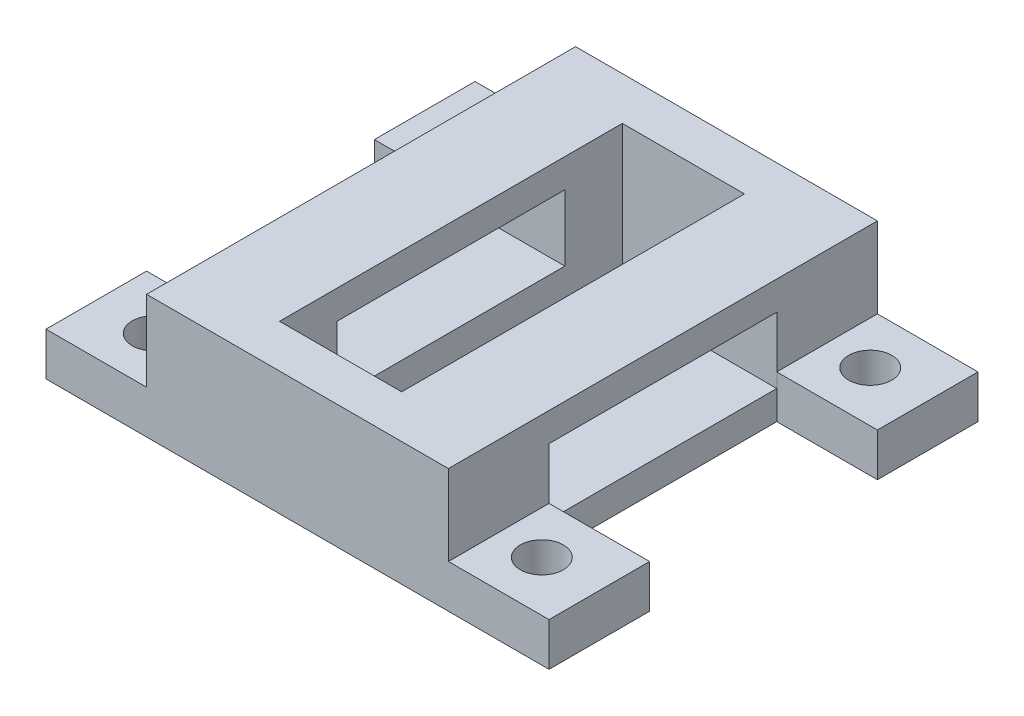
SolidWorks part; units mm, degrees
ref_plane "Front Plane" through (0, 0, 0) normal (0, 0, 1) x (1, 0, 0)
ref_plane "Top Plane" through (0, 0, 0) normal (0, 1, 0) x (1, 0, 0)
ref_plane "Right Plane" through (0, 0, 0) normal (1, 0, 0) x (0, 0, -1)
sketch "Sketch1" plane through (0, 0, 0) normal (0, 1, 0) x (1, 0, 0)
  line L8 (-10.5, 0) -> (-10.5, -24.8496)
  line L10 (10.5, 0) -> (10.5, -24.8496)
  line L11 (7.5, -29.8496) -> (-10.5, -29.8496)
  line L14 (7.5, -29.8496) -> (10.5, -29.8496)
  line L20 (10.5, 0) -> (-10.5, 0)
  line L21 (10.5, -24.8496) -> (10.5, -29.8496)
  line L22 (-10.5, -24.8496) -> (-10.5, -29.8496)
  point P0 (0, 0)
  point P1 (0, 0)
  dimension "D4" = 30
  dimension "D5" = 21
extrude "Boss-Extrude1" add sketch "Sketch1" along normal blind 8.6
sketch "Sketch5" plane through (0, 8.6, 0) normal (0, 1, 0) x (1, 0, 0)
  line L0 (10.5, 0) -> (-10.5, 0) construction
  line L1 (4.25, -26.8496) -> (-4.25, -26.8496)
  line L2 (4.25, -26.8496) -> (4.25, -2.9996)
  line L3 (4.25, -2.9996) -> (-4.25, -2.9996)
  line L4 (-4.25, -26.8496) -> (-4.25, -2.9996)
  line L8 (-10.5, -29.8496) -> (10.5, -29.8496) construction
  dimension "D1" = 3
  dimension "D2" = 23.85
  dimension "D3" = 8.5
  dimension "D4" = 6.25
  dimension "D5" = 6.25
  dimension "D6" = 2.9996
extrude "Cut-Extrude3" cut sketch "Sketch5" against normal blind 10
sketch "Sketch6" plane through (-10.5, 0, 0) normal (-1, 0, 0) x (0, 0, 1)
  line L1 (7, 2) -> (22.85, 2)
  line L2 (7, 2) -> (7, 6.6)
  line L3 (7, 6.6) -> (22.85, 6.6)
  line L4 (22.85, 2) -> (22.85, 6.6)
  line L5 (0, 0) -> (29.8496, 0) construction
  line L6 (0, 8.6) -> (29.8496, 8.6) construction
  line L7 (0, 8.6) -> (0, 0) construction
  dimension "D1" = 15.85
  dimension "D2" = 7
  dimension "D3" = 4.6
  dimension "D4" = 2
  dimension "D5" = 2
extrude "Cut-Extrude4" cut sketch "Sketch6" against normal blind 10
sketch "Sketch7" plane through (10.5, 0, 0) normal (1, 0, 0) x (0, 0, -1)
  line L1 (-22.8496, 6.6) -> (-6.9996, 6.6)
  line L2 (-22.8496, 6.6) -> (-22.8496, 2)
  line L3 (-22.8496, 2) -> (-6.9996, 2)
  line L4 (-6.9996, 6.6) -> (-6.9996, 2)
  line L5 (-29.8496, 0) -> (0, 0) construction
  line L6 (-29.8496, 8.6) -> (-29.8496, 0) construction
  line L7 (-29.8496, 8.6) -> (0, 8.6) construction
  dimension "D1" = 15.85
  dimension "D2" = 7
  dimension "D3" = 2
  dimension "D4" = 4.6
  dimension "D5" = 2
extrude "Cut-Extrude5" cut sketch "Sketch7" against normal blind 10
sketch "Sketch9" plane through (0, 0, 0) normal (0, -1, 0) x (1, 0, 0)
  line L11 (-10.5, 29.8496) -> (-17.5, 29.8496)
  line L12 (-10.5, 29.8496) -> (-10.5, 22.8496)
  line L13 (-10.5, 22.8496) -> (-17.5, 22.8496)
  line L14 (-17.5, 29.8496) -> (-17.5, 22.8496)
  line L15 (10.5, 29.8496) -> (17.5, 29.8496)
  line L16 (10.5, 29.8496) -> (10.5, 22.8496)
  line L17 (10.5, 22.8496) -> (17.5, 22.8496)
  line L18 (17.5, 29.8496) -> (17.5, 22.8496)
  line L19 (-10.5, 0) -> (-17.5, 0)
  line L20 (-10.5, 0) -> (-10.5, 7)
  line L21 (-10.5, 7) -> (-17.5, 7)
  line L22 (-17.5, 0) -> (-17.5, 7)
  line L23 (10.5, 0) -> (17.5, 0)
  line L24 (10.5, 0) -> (10.5, 7)
  line L25 (10.5, 7) -> (17.5, 7)
  line L26 (17.5, 0) -> (17.5, 7)
  dimension "D1" = 7
  dimension "D2" = 7
  dimension "D3" = 7
  dimension "D4" = 7
  dimension "D5" = 7
  dimension "D6" = 7
  dimension "D7" = 7
  dimension "D8" = 7
extrude "Boss-Extrude3" add sketch "Sketch9" against normal blind 3
sketch "Sketch10" plane through (0, 3, 0) normal (0, 1, 0) x (1, 0, 0)
  line L0 (0, 5.3476) -> (0, -5.3476) construction
  line L1 (10.5, 0) -> (17.5, 0) construction
  line L4 (10.5, -22.8496) -> (17.5, -22.8496) construction
  circle A0 centre (-13.5, -3.5) radius 1.5
  circle A1 centre (-13.5, -26.3496) radius 1.5
  circle A2 centre (13.5, -26.3496) radius 1.5
  circle A3 centre (13.5, -3.5) radius 1.5
  point P10 (0, 0)
  dimension "D1" = 27
  dimension "D2" = 27
  dimension "D3" = 3.5
  dimension "D4" = 22.8496
  dimension "D5" = 3.5
extrude "Cut-Extrude6" cut sketch "Sketch10" against normal blind 3
